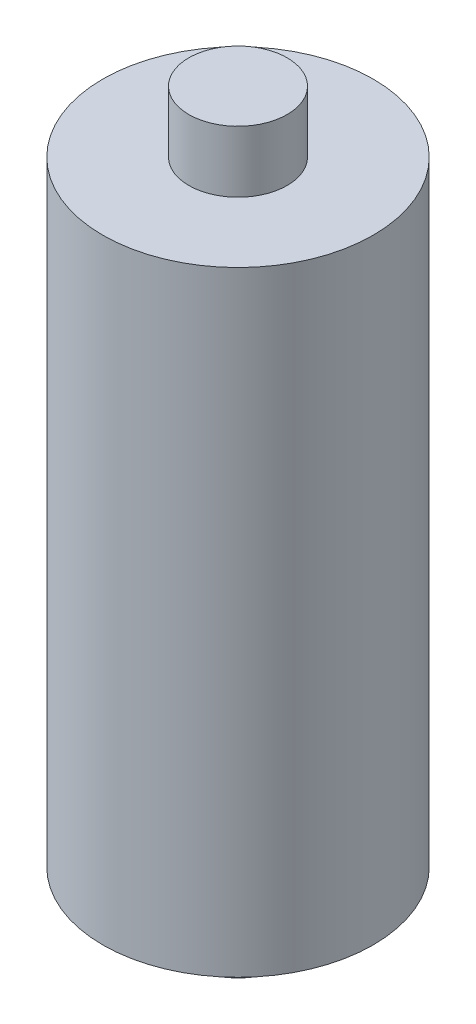
SolidWorks part; units mm, degrees
ref_plane "前视基准面" through (0, 0, 0) normal (0, 0, 1) x (1, 0, 0)
ref_plane "上视基准面" through (0, 0, 0) normal (0, 1, 0) x (1, 0, 0)
ref_plane "右视基准面" through (0, 0, 0) normal (1, 0, 0) x (0, 0, -1)
sketch "草图1" plane through (0, 0, 0) normal (0, 1, 0) x (1, 0, 0)
  circle A0 centre (0, 0) radius 11
  dimension "D1" = 22
extrude "凸台-拉伸1" add sketch "草图1" along normal mid plane 50
sketch "草图2" plane through (0, 25, 0) normal (0, 1, 0) x (1, 0, 0)
  circle A0 centre (0, 0) radius 4
  dimension "D1" = 8
extrude "凸台-拉伸2" add sketch "草图2" along normal blind 5
mirror "镜向1" about plane through (0, 0, 0) normal (0, 1, 0) of "凸台-拉伸2"
